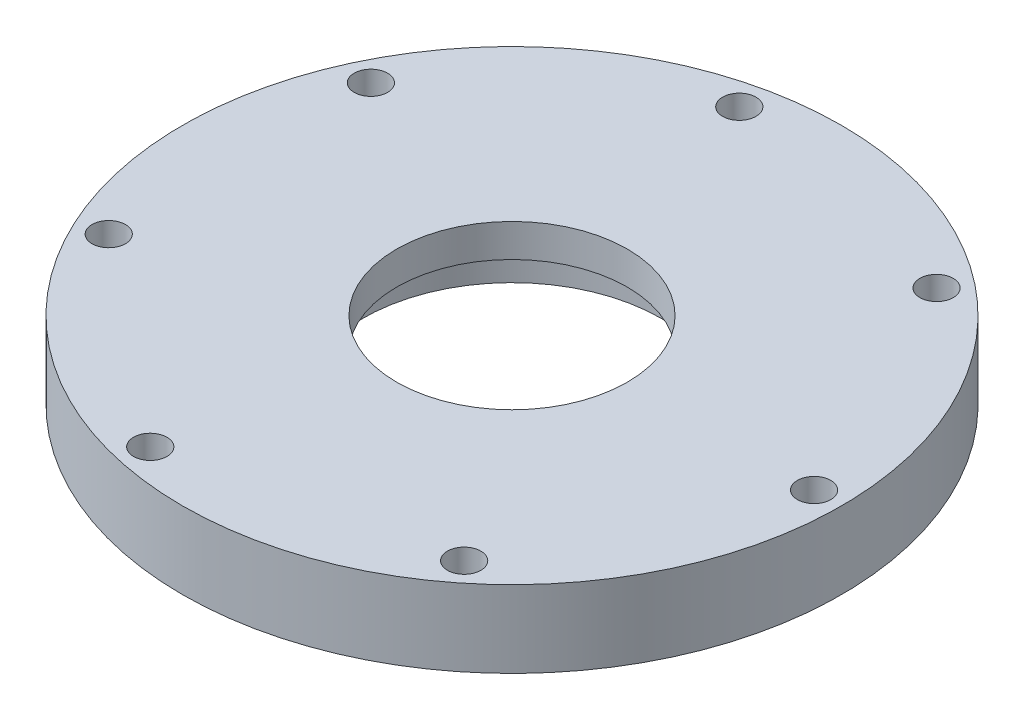
SolidWorks part; units mm, degrees
ref_plane "Alzado" through (0, 0, 0) normal (0, 0, 1) x (1, 0, 0)
ref_plane "Planta" through (0, 0, 0) normal (0, 1, 0) x (1, 0, 0)
ref_plane "Vista lateral" through (0, 0, 0) normal (1, 0, 0) x (0, 0, -1)
sketch "Croquis1" plane through (0, 0, 0) normal (0, 1, 0) x (1, 0, 0)
  circle A0 centre (0, 0) radius 30
  circle A1 centre (0, 0) radius 10.5
  dimension "D1" = 60
  dimension "D2" = 21
extrude "Saliente-Extruir1" add sketch "Croquis1" along normal blind 7
sketch "Croquis2" plane through (0, 0, 0) normal (0, -1, 0) x (1, 0, 0)
  circle A0 centre (0, 0) radius 13.575
  dimension "D1" = 27.15
extrude "Cortar-Extruir1" cut sketch "Croquis2" against normal blind 4
sketch "Croquis3" plane through (0, 7, 0) normal (0, 1, 0) x (1, 0, 0)
  circle A0 centre (27.5, 0) radius 1.52
  circle A1 centre (17.146, -21.5004) radius 1.52
  circle A2 centre (-6.1193, -26.8105) radius 1.52
  circle A3 centre (-24.7766, -11.9318) radius 1.52
  circle A4 centre (-24.7766, 11.9318) radius 1.52
  circle A5 centre (-6.1193, 26.8105) radius 1.52
  circle A6 centre (17.146, 21.5004) radius 1.52
  point P18 (0, 0)
  dimension "D2" = 3.04
  dimension "D1" = 27.5
  dimension "D3" = 7
extrude "Cortar-Extruir2" cut sketch "Croquis3" against normal through all
sketch "Croquis4" plane through (0, 7, 0) normal (0, 1, 0) x (1, 0, 0)
  circle A0 centre (0, 0) radius 17.5
  circle A1 centre (0, 0) radius 15
  dimension "D1" = 35
  dimension "D2" = 30
extrude "Saliente-Extruir2" [suppressed] add sketch "Croquis4" along normal blind 5
